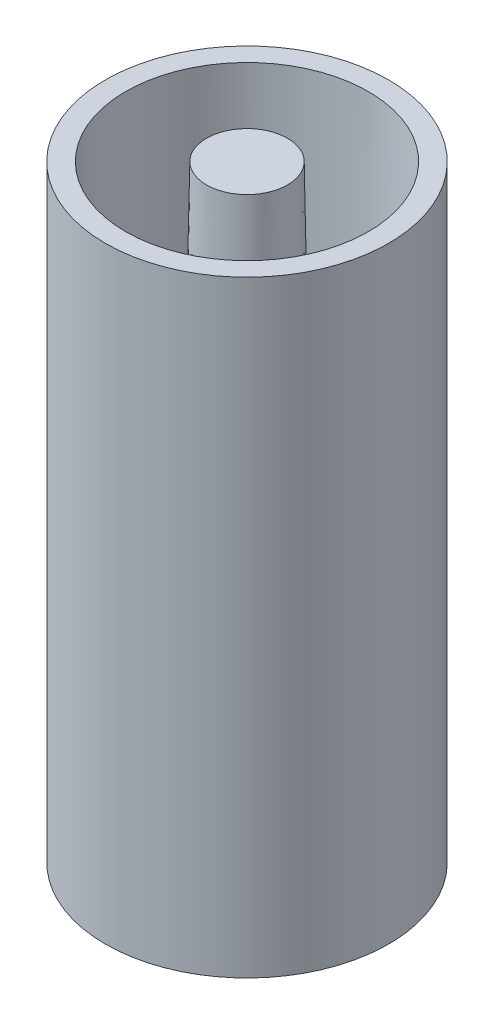
SolidWorks part; units mm, degrees
ref_plane "Front Plane" through (0, 0, 0) normal (0, 0, 1) x (1, 0, 0)
ref_plane "Top Plane" through (0, 0, 0) normal (0, 1, 0) x (1, 0, 0)
ref_plane "Right Plane" through (0, 0, 0) normal (1, 0, 0) x (0, 0, -1)
sketch "Sketch1" plane through (0, 0, 0) normal (0, 1, 0) x (1, 0, 0)
  circle A0 centre (0, 0) radius 22.225
  dimension "D1" = 44.45
extrude "Boss-Extrude1" add sketch "Sketch1" along normal blind 95.25
sketch "Sketch6" plane through (0, 95.25, 0) normal (0, 1, 0) x (1, 0, 0)
  circle A0 centre (0, 0) radius 19.05
  circle A1 centre (0, 0) radius 6.35
extrude "Cut-Extrude1" cut sketch "Sketch6" against normal blind 88.9 draft 1
